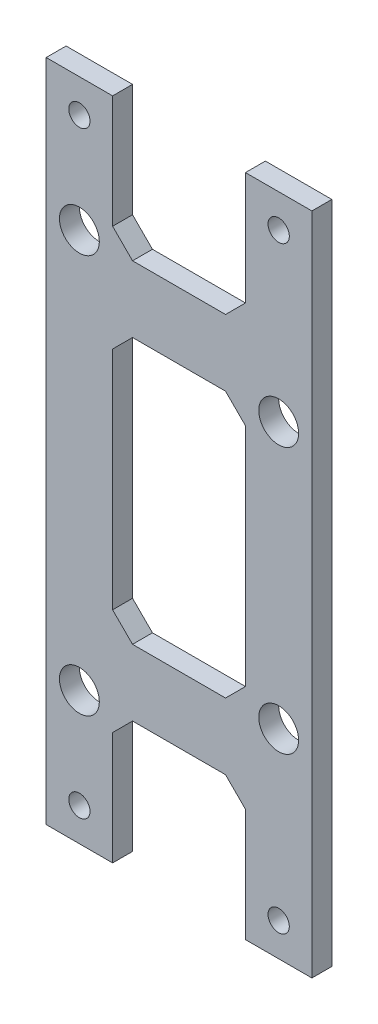
SolidWorks part; units mm, degrees
ref_plane "正面" through (0, 0, 0) normal (0, 0, 1) x (1, 0, 0)
ref_plane "平面" through (0, 0, 0) normal (0, 1, 0) x (1, 0, 0)
ref_plane "右側面" through (0, 0, 0) normal (1, 0, 0) x (0, 0, -1)
sketch "ｽｹｯﾁ1" plane through (0, 0, 0) normal (0, 0, 1) x (1, 0, 0)
  line L1 (0, 0) -> (40, 0)
  line L2 (0, 0) -> (0, 100)
  line L3 (0, 100) -> (40, 100)
  line L4 (40, 0) -> (40, 100)
  circle A0 centre (5, 95) radius 1.6
  circle A1 centre (35, 95) radius 1.6
  circle A2 centre (5, 80) radius 3
  circle A3 centre (35, 70) radius 3
  circle A4 centre (5, 20) radius 3
  circle A5 centre (35, 30) radius 3
  circle A6 centre (5, 5) radius 1.6
  circle A7 centre (35, 5) radius 1.6
  dimension "D3" = 5
  dimension "D4" = 3.2
  dimension "D5" = 5
  dimension "D6" = 15
  dimension "D7" = 5
  dimension "D8" = 6
  dimension "D9" = 6
  dimension "D10" = 5
  dimension "D11" = 25
  dimension "D13" = 5
  dimension "D14" = 3.2
  dimension "D15" = 3.2
  dimension "D16" = 5
  dimension "D17" = 5
  dimension "D18" = 5
  dimension "D19" = 3.2
  dimension "D20" = 5
  dimension "D21" = 5
  dimension "D22" = 25
  dimension "D23" = 6
  dimension "D24" = 5
  dimension "D25" = 6
  dimension "D26" = 5
  dimension "D27" = 15
  dimension "D1" = 100
  dimension "D2" = 40
  dimension "D12" = 5
extrude "ﾎﾞｽ - 押し出し1" add sketch "ｽｹｯﾁ1" along normal blind 3
sketch "ｽｹｯﾁ2" plane through (0, 0, 3) normal (0, 0, 1) x (1, 0, 0)
  line L0 (0, 100) -> (0, 0) construction
  line L1 (10, 100) -> (30, 100)
  line L2 (10, 100) -> (10, 80)
  line L3 (10, 80) -> (30, 80)
  line L4 (30, 100) -> (30, 80)
  line L5 (10, 20) -> (30, 20)
  line L6 (10, 20) -> (10, 0)
  line L7 (10, 0) -> (30, 0)
  line L8 (30, 20) -> (30, 0)
  line L9 (40, 0) -> (40, 100) construction
  line L12 (40, 100) -> (0, 100) construction
  line L13 (0, 0) -> (40, 0) construction
  dimension "D1" = 10
  dimension "D2" = 10
  dimension "D3" = 20
  dimension "D4" = 0
  dimension "D5" = 0
  dimension "D6" = 10
  dimension "D7" = 10
  dimension "D8" = 20
extrude "ｶｯﾄ - 押し出し1" cut sketch "ｽｹｯﾁ2" against normal through all
sketch "ｽｹｯﾁ3" plane through (0, 0, 3) normal (0, 0, 1) x (1, 0, 0)
  line L0 (0, 100) -> (0, 0) construction
  line L1 (30, 30) -> (10, 30)
  line L2 (30, 30) -> (30, 70)
  line L3 (30, 70) -> (10, 70)
  line L4 (10, 30) -> (10, 70)
  line L5 (40, 0) -> (40, 100) construction
  line L6 (10, 80) -> (30, 80) construction
  line L7 (30, 20) -> (10, 20) construction
  dimension "D1" = 10
  dimension "D2" = 10
  dimension "D3" = 10
  dimension "D4" = 10
extrude "ｶｯﾄ - 押し出し2" cut sketch "ｽｹｯﾁ3" against normal blind 10
chamfer "面取り1" distance 3 angle 45 8 edges at (10, 20, 1.5) (30, 20, 1.5) (10, 80, 1.5) (30, 80, 1.5) (30, 70, 1.5) (10, 70, 1.5) (10, 30, 1.5) (30, 30, 1.5)
